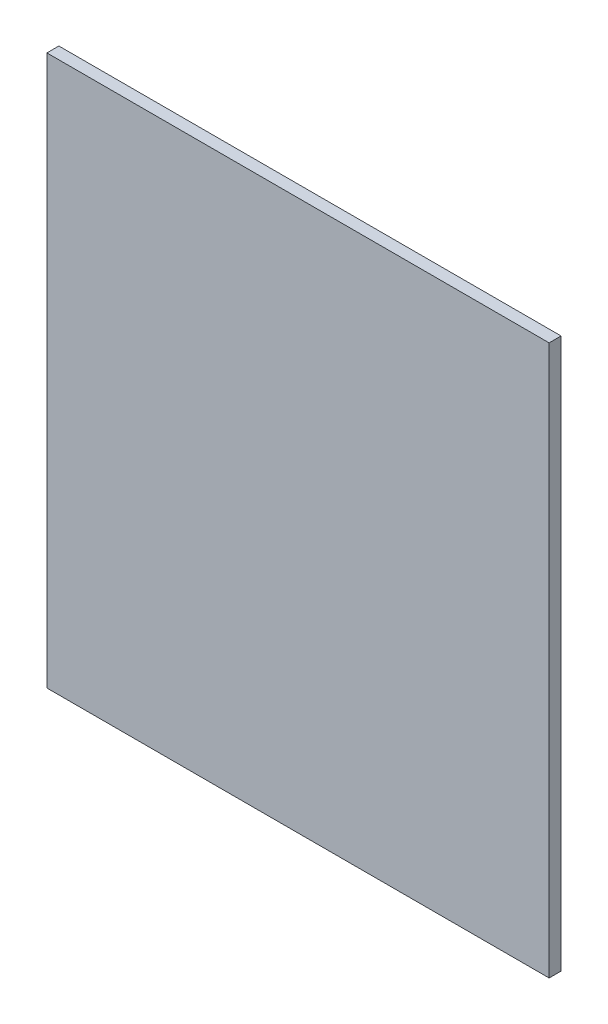
SolidWorks part; units mm, degrees
material "Acrylic (Medium-high impact)"
ref_plane "Front Plane" through (0, 0, 0) normal (0, 0, 1) x (1, 0, 0)
ref_plane "Top Plane" through (0, 0, 0) normal (0, 1, 0) x (1, 0, 0)
ref_plane "Right Plane" through (0, 0, 0) normal (1, 0, 0) x (0, 0, -1)
sketch "Sketch1" plane through (0, 0, 0) normal (0, 0, 1) x (1, 0, 0)
  line L1 (0, 0) -> (533.4, 0)
  line L2 (0, 0) -> (0, 584.2)
  line L3 (0, 584.2) -> (533.4, 584.2)
  line L4 (533.4, 0) -> (533.4, 584.2)
  dimension "D1" = 533.4
  dimension "D2" = 584.2
extrude "Boss-Extrude1" add sketch "Sketch1" along normal blind 12.7
